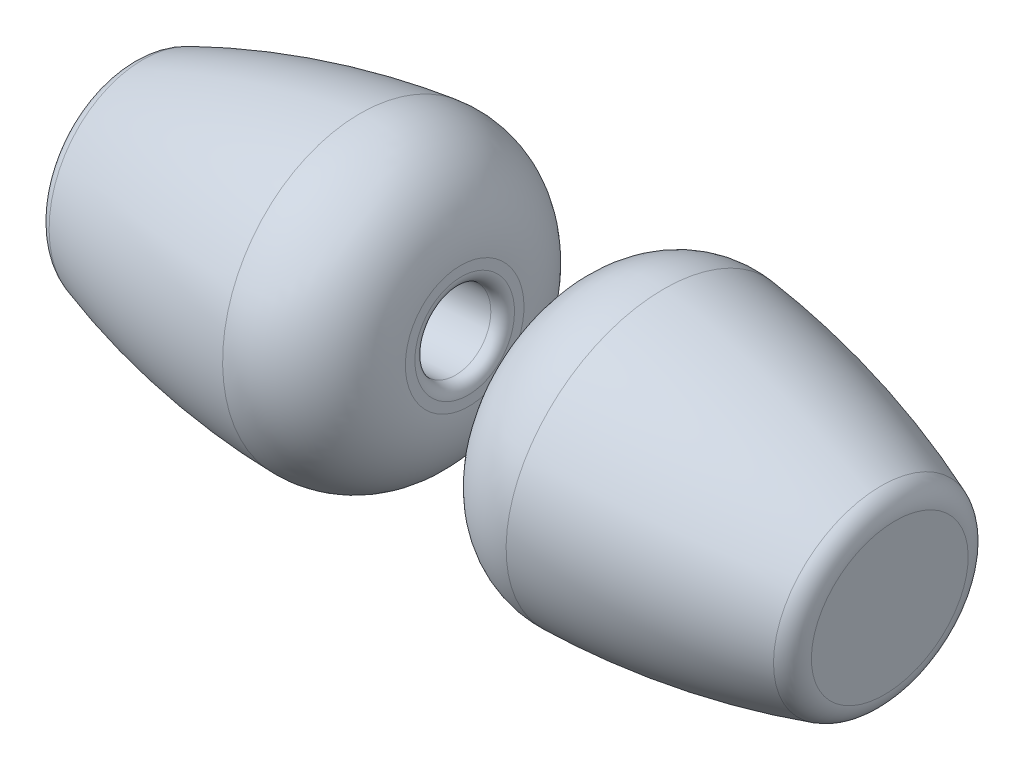
SolidWorks part; units mm, degrees
ref_plane "front" through (0, 0, 0) normal (0, 0, 1) x (1, 0, 0)
ref_plane "top" through (0, 0, 0) normal (0, 1, 0) x (1, 0, 0)
ref_plane "right" through (0, 0, 0) normal (1, 0, 0) x (0, 0, -1)
sketch "sketch1" plane through (0, 0, 0) normal (0, 0, 1) x (1, 0, 0)
  line L0 (0, 0) -> (0, 191.7552) construction
  line L1 (5, 160.1093) -> (40.914, 157.6226) construction
  line L2 (40.914, 157.6226) -> (30, 0) construction
  line L3 (27.506, 0.1727) -> (38.5804, 160.1115) construction
  line L4 (27.506, 0.1727) -> (30, 0) construction
  line L5 (5, 160.1093) -> (4.8273, 157.6153) construction
  line L6 (4.8273, 157.6153) -> (-19.3231, 159.2875) construction
  line L7 (24.0182, -50.199) -> (31.2919, 54.8506) construction
  circle A0 centre (27.506, 0.1727) radius 2.5 construction
  spline S0 degree 3 poles (4.8273, 157.6153) (36.4183, 155.4279) (39.0186, 166.4413) (27.506, 0.1727) knots 0 0 0 0 1 1 1 1
  dimension "D5" = 5
  dimension "D6" = 95
  dimension "D7" = 500
  dimension "D1" = 30
  dimension "D2" = 10
  dimension "D3" = 36
  dimension "D4" = 158
ref_plane "plane1" through (27.506, 0.1727, 0) normal (-0.0691, -0.9976, 0) x (-0.9976, 0.0691, 0)
sketch "sketch2" plane through (27.506, 0.1727, 0) normal (-0.0691, -0.9976, 0) x (-0.9976, 0.0691, 0)
  circle A0 centre (0, 0) radius 2.5
  dimension "D1" = 5
sketch "sketch9" plane through (0, 0, 0) normal (0, 0, 1) x (1, 0, 0)
  line L0 (2, 157.8111) -> (2.1727, 160.3051)
  line L1 (4.8273, 157.6153) -> (-19.3231, 159.2875) construction
  line L2 (6.4204, 163.7449) -> (16.2429, 160.8345) construction
  line L3 (16.2429, 160.8345) -> (15.9666, 156.844)
  line L4 (15.9666, 156.844) -> (2, 157.8111)
  line L5 (0, 0) -> (0, 191.7552) construction
  line L6 (6.4204, 163.7449) -> (5.9904, 157.5348) construction
  arc A0 (6.4204, 163.7449) -> (2.1727, 160.3051) centre (5.8982, 160.0471) ccw
  arc A1 (16.2429, 160.8345) -> (6.4204, 163.7449) centre (1.5553, 129.2956) ccw
  dimension "D1" = 2
  dimension "D2" = 6.225
  dimension "D3" = 4
  dimension "D4" = 14
  dimension "D5" = 10
  dimension "D6" = 2.5
revolve "revolve1" add sketch "sketch9" angle 360 about L4
fillet "fillet1" radius 1 1 edges at (16.2429, 160.8345, 0)
sketch "sketch10" plane through (-8.8845, 0.6152, 0) normal (-0.9976, 0.0691, 0) x (0, 0, 1)
  circle A0 centre (0, 157.5723) radius 1.6
  circle A1 centre (0, 157.5723) radius 2.5 construction
  dimension "D1" = 3.2
extrude "extrudecut" cut sketch "sketch10" against normal blind 10
fillet "fillet2" radius 0.5 1 edges at (1.8895, 156.2149, 0)
mirror "simetric" about plane through (0, 0, 0) normal (1, 0, 0) of bodies 135
